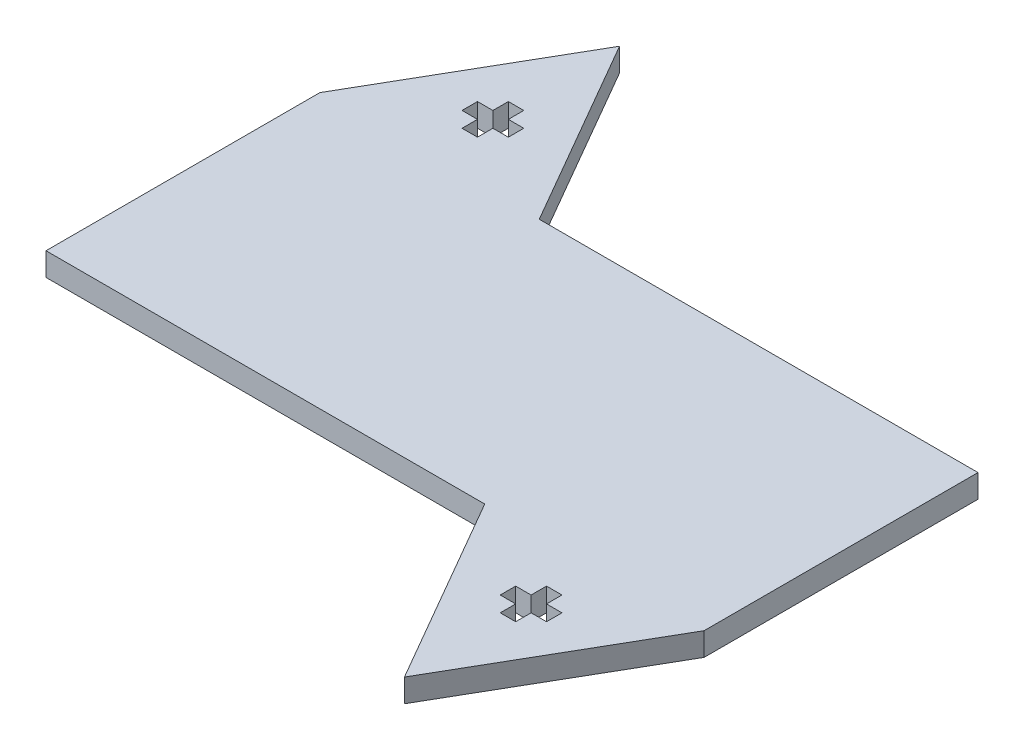
SolidWorks part; units mm, degrees
ref_plane "Front Plane" through (0, 0, 0) normal (0, 0, 1) x (1, 0, 0)
ref_plane "Top Plane" through (0, 0, 0) normal (0, 1, 0) x (1, 0, 0)
ref_plane "Right Plane" through (0, 0, 0) normal (1, 0, 0) x (0, 0, -1)
sketch "Sketch1" plane through (0, 0, 0) normal (0, 1, 0) x (1, 0, 0)
  line L0 (-108.23, 57.853) -> (-108.23, -32.3069) construction
  line L1 (-108.23, 57.853) -> (36.19, 57.853)
  line L2 (-180.44, 57.853) -> (-180.44, -32.3069)
  line L3 (-180.44, -32.3069) -> (-36.02, -32.3069)
  line L4 (36.19, 57.853) -> (36.19, -32.3069)
  line L5 (-36.02, 57.853) -> (-36.02, -32.3069) construction
  line L6 (-180.44, 57.853) -> (-144.335, 120.3886)
  line L7 (-144.335, 120.3886) -> (-108.23, 57.853)
  line L8 (-36.02, -32.3069) -> (0.085, -94.8426)
  line L9 (0.085, -94.8426) -> (36.19, -32.3069)
  line L10 (-180.44, 57.853) -> (-108.23, 57.853) construction
  line L11 (-180.44, 78.6975) -> (-108.23, 78.6975) construction
  line L12 (-36.02, -32.3069) -> (36.19, -32.3069) construction
  line L13 (-36.02, -53.1514) -> (36.19, -53.1514) construction
  line L14 (7.705, -50.6114) -> (7.705, -55.6914)
  line L15 (7.705, -55.6914) -> (2.625, -55.6914)
  line L16 (2.625, -55.6914) -> (2.625, -60.7714)
  line L17 (2.625, -60.7714) -> (-2.455, -60.7714)
  line L18 (-2.455, -60.7714) -> (-2.455, -55.6914)
  line L19 (-2.455, -55.6914) -> (-7.535, -55.6914)
  line L20 (-7.535, -55.6914) -> (-7.535, -50.6114)
  line L21 (-2.455, -50.6114) -> (-7.535, -50.6114)
  line L22 (-2.455, -45.5314) -> (-2.455, -50.6114)
  line L23 (2.625, -45.5314) -> (-2.455, -45.5314)
  line L24 (2.625, -50.6114) -> (2.625, -45.5314)
  line L25 (7.705, -50.6114) -> (2.625, -50.6114)
  line L26 (-146.875, 81.2375) -> (-151.955, 81.2375)
  line L27 (-141.795, 71.0775) -> (-146.875, 71.0775)
  line L28 (-146.875, 71.0775) -> (-146.875, 76.1575)
  line L29 (-136.715, 81.2375) -> (-136.715, 76.1575)
  line L30 (-146.875, 86.3175) -> (-146.875, 81.2375)
  line L31 (-141.795, 81.2375) -> (-141.795, 86.3175)
  line L32 (-136.715, 81.2375) -> (-141.795, 81.2375)
  line L33 (-146.875, 76.1575) -> (-151.955, 76.1575)
  line L34 (-136.715, 76.1575) -> (-141.795, 76.1575)
  line L35 (-151.955, 76.1575) -> (-151.955, 81.2375)
  line L36 (-141.795, 76.1575) -> (-141.795, 71.0775)
  line L37 (-141.795, 86.3175) -> (-146.875, 86.3175)
  point P14 (-144.335, 78.6975)
  point P15 (0.085, -53.1514)
  point P16 (-144.335, 78.6975)
  point P25 (-7.535, -53.1514)
  point P30 (7.705, -53.1514)
  point P39 (-151.955, 78.6975)
  point P44 (-136.715, 78.6975)
  dimension "D1" = 216.63
  dimension "D2" = 90.1598
  dimension "D3" = 72.21
  dimension "D4" = 72.21
  dimension "D5" = 72.21
  dimension "D6" = 72.21
  dimension "D7" = 72.21
  dimension "D8" = 72.21
  dimension "D11" = 2.54
  dimension "D12" = 5.08
  dimension "D13" = 5.08
  dimension "D14" = 5.08
  dimension "D15" = 7.62
  dimension "D16" = 15.24
  dimension "D17" = 5.08
  dimension "D18" = 2.54
  dimension "D19" = 5.08
  dimension "D20" = 5.08
  dimension "D21" = 5.08
  dimension "D22" = 7.62
  dimension "D23" = 15.24
  dimension "D24" = 5.08
  dimension "D9" = 20.8445
  dimension "D10" = 20.8445
extrude "Boss-Extrude1" add sketch "Sketch1" along normal blind 7.62
sketch "Sketch2" plane through (0, 7.62, 0) normal (0, 1, 0) x (1, 0, 0)
  line L0 (-108.23, 57.853) -> (-108.23, -32.3069) construction
  line L1 (-180.44, -32.3069) -> (-36.02, -32.3069) construction
  line L2 (-36.02, -32.3069) -> (-36.02, 57.853) construction
  line L3 (36.19, 57.853) -> (-108.23, 57.853) construction
  line L4 (36.19, -32.3069) -> (-36.02, -32.3069) construction
  line L5 (-108.23, 57.853) -> (-180.44, 57.853) construction
  line L6 (-180.44, 57.853) -> (-180.44, -32.3069) construction
  line L7 (-180.44, -27.2269) -> (36.19, -27.2269) construction
  line L8 (36.19, -32.3069) -> (36.19, 57.853) construction
  line L9 (36.19, 52.773) -> (-180.44, 52.773) construction
  line L10 (-180.44, 12.773) -> (36.19, 12.773) construction
  line L11 (-180.44, -23.3331) -> (36.19, -23.3331) construction
  line L12 (-180.44, 48.8791) -> (36.19, 48.8791) construction
  dimension "D1" = 5.08
  dimension "D2" = 5.08
  dimension "D3" = 36.1061
  dimension "D4" = 36.1061
